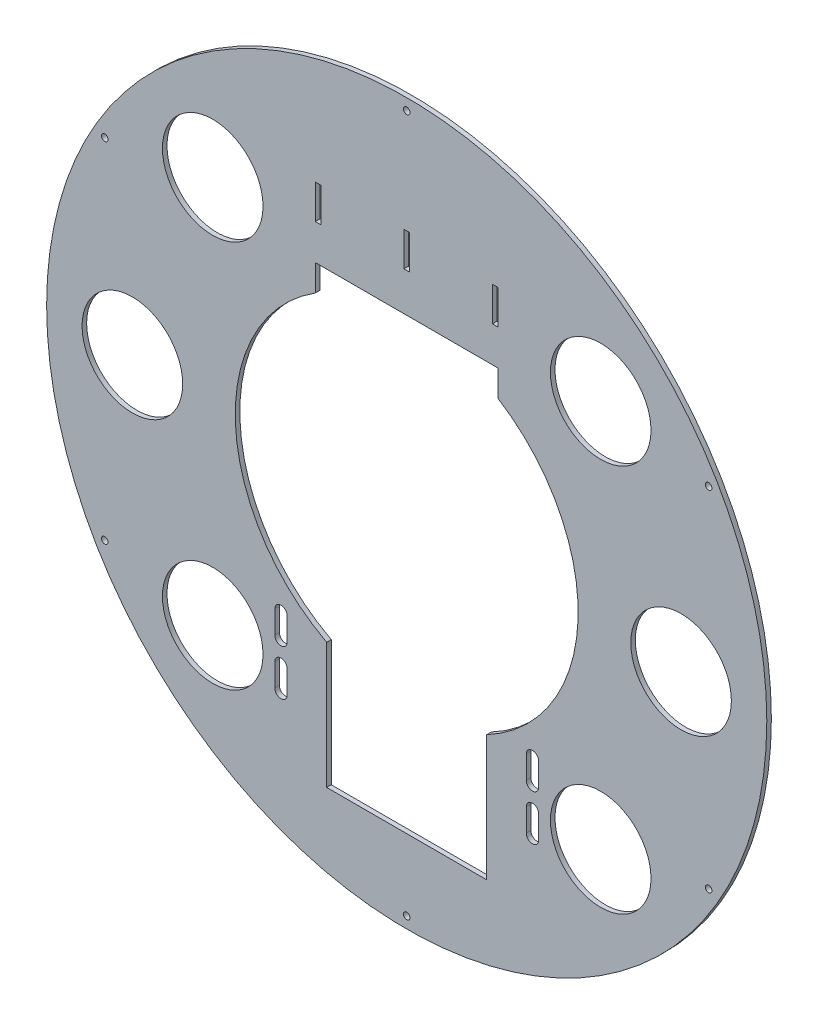
SolidWorks part; units mm, degrees
ref_plane "Front Plane" through (0, 0, 0) normal (0, 0, 1) x (1, 0, 0)
ref_plane "Top Plane" through (0, 0, 0) normal (0, 1, 0) x (1, 0, 0)
ref_plane "Right Plane" through (0, 0, 0) normal (1, 0, 0) x (0, 0, -1)
sketch "Sketch1" plane through (0, 0, 0) normal (0, 0, 1) x (-1, 0, 0)
  arc A4 (0, -200.025) -> (0, 200.025) centre (0, 0) ccw
  arc A5 (0, 200.025) -> (0, -200.025) centre (0, 0) ccw
  arc A16 (167.6449, 98.6533) -> (167.8101, 95.0217) centre (167.7275, 96.8375) ccw
  arc A17 (167.8101, 95.0217) -> (167.6449, 98.6533) centre (167.7275, 96.8375) ccw
  arc A18 (-1.6138, 194.5114) -> (1.6138, 192.8386) centre (0, 193.675) ccw
  arc A19 (1.6138, 192.8386) -> (-1.6138, 194.5114) centre (0, 193.675) ccw
  arc A20 (-169.2587, 95.8581) -> (-166.1962, 97.8169) centre (-167.7275, 96.8375) ccw
  arc A21 (-166.1962, 97.8169) -> (-169.2587, 95.8581) centre (-167.7275, 96.8375) ccw
  arc A22 (-167.6449, -98.6533) -> (-167.8101, -95.0217) centre (-167.7275, -96.8375) ccw
  arc A23 (-167.8101, -95.0217) -> (-167.6449, -98.6533) centre (-167.7275, -96.8375) ccw
  arc A24 (1.6138, -194.5114) -> (-1.6138, -192.8386) centre (0, -193.675) ccw
  arc A25 (-1.6138, -192.8386) -> (1.6138, -194.5114) centre (0, -193.675) ccw
  arc A26 (169.2587, -95.8581) -> (166.1962, -97.8169) centre (167.7275, -96.8375) ccw
  arc A27 (166.1962, -97.8169) -> (169.2587, -95.8581) centre (167.7275, -96.8375) ccw
  point P0 (0, 193.675)
sketch "Sketch2" plane through (0, 0, 0) normal (0, 0, 1) x (1, 0, 0)
  line L0 (-69.85, -82.55) -> (-69.85, -95.25) construction
  line L1 (-44.45, -84.2423) -> (44.45, -84.2423)
  line L2 (-44.45, -84.2423) -> (-44.45, -154.0923)
  line L3 (-44.45, -154.0923) -> (44.45, -154.0923)
  line L4 (44.45, -84.2423) -> (44.45, -154.0923)
  line L5 (-66.421, -82.55) -> (-66.421, -95.25)
  line L6 (-73.279, -82.55) -> (-73.279, -95.25)
  line L7 (69.85, -82.55) -> (69.85, -95.25) construction
  line L8 (73.279, -82.55) -> (73.279, -95.25)
  line L9 (66.421, -82.55) -> (66.421, -95.25)
  line L10 (-69.85, -107.95) -> (-69.85, -120.65) construction
  line L11 (-66.421, -107.95) -> (-66.421, -120.65)
  line L12 (-73.279, -107.95) -> (-73.279, -120.65)
  line L13 (69.85, -107.95) -> (69.85, -120.65) construction
  line L14 (73.279, -107.95) -> (73.279, -120.65)
  line L15 (66.421, -107.95) -> (66.421, -120.65)
  line L16 (-76.9302, -101.6) -> (80.7091, -101.6) construction
  line L18 (-50.8, 95.25) -> (50.8, 95.25)
  line L19 (-50.8, 95.25) -> (-50.8, 80.5725)
  line L20 (-50.8, 80.5725) -> (50.8, 80.5725)
  line L21 (50.8, 95.25) -> (50.8, 80.5725)
  circle A0 centre (0, 0) radius 95.25
  arc A1 (-66.421, -82.55) -> (-73.279, -82.55) centre (-69.85, -82.55) ccw
  arc A2 (1.6138, -194.5114) -> (-1.6138, -192.8386) centre (0, -193.675) ccw
  arc A3 (-1.6138, -192.8386) -> (1.6138, -194.5114) centre (0, -193.675) ccw
  arc A4 (1.6138, -194.5114) -> (-1.6138, -192.8386) centre (0, -193.675) ccw
  arc A5 (-1.6138, -192.8386) -> (1.6138, -194.5114) centre (0, -193.675) ccw
  arc A6 (-167.6449, -98.6533) -> (-167.8101, -95.0217) centre (-167.7275, -96.8375) ccw
  arc A7 (-167.8101, -95.0217) -> (-167.6449, -98.6533) centre (-167.7275, -96.8375) ccw
  arc A8 (-167.6449, -98.6533) -> (-167.8101, -95.0217) centre (-167.7275, -96.8375) ccw
  arc A9 (-167.8101, -95.0217) -> (-167.6449, -98.6533) centre (-167.7275, -96.8375) ccw
  arc A10 (0, 200.025) -> (0, -200.025) centre (0, 0) ccw
  arc A11 (0, -200.025) -> (0, 200.025) centre (0, 0) ccw
  arc A12 (0, 200.025) -> (0, -200.025) centre (0, 0) ccw
  arc A13 (0, -200.025) -> (0, 200.025) centre (0, 0) ccw
  arc A14 (167.6449, 98.6533) -> (167.8101, 95.0217) centre (167.7275, 96.8375) ccw
  arc A15 (167.8101, 95.0217) -> (167.6449, 98.6533) centre (167.7275, 96.8375) ccw
  arc A16 (167.6449, 98.6533) -> (167.8101, 95.0217) centre (167.7275, 96.8375) ccw
  arc A17 (167.8101, 95.0217) -> (167.6449, 98.6533) centre (167.7275, 96.8375) ccw
  arc A18 (169.2587, -95.8581) -> (166.1962, -97.8169) centre (167.7275, -96.8375) ccw
  arc A19 (166.1962, -97.8169) -> (169.2587, -95.8581) centre (167.7275, -96.8375) ccw
  arc A20 (169.2587, -95.8581) -> (166.1962, -97.8169) centre (167.7275, -96.8375) ccw
  arc A21 (166.1962, -97.8169) -> (169.2587, -95.8581) centre (167.7275, -96.8375) ccw
  arc A22 (-169.2587, 95.8581) -> (-166.1962, 97.8169) centre (-167.7275, 96.8375) ccw
  arc A23 (-166.1962, 97.8169) -> (-169.2587, 95.8581) centre (-167.7275, 96.8375) ccw
  arc A24 (-169.2587, 95.8581) -> (-166.1962, 97.8169) centre (-167.7275, 96.8375) ccw
  arc A25 (-166.1962, 97.8169) -> (-169.2587, 95.8581) centre (-167.7275, 96.8375) ccw
  arc A26 (-1.6138, 194.5114) -> (1.6138, 192.8386) centre (0, 193.675) ccw
  arc A27 (1.6138, 192.8386) -> (-1.6138, 194.5114) centre (0, 193.675) ccw
  arc A28 (-1.6138, 194.5114) -> (1.6138, 192.8386) centre (0, 193.675) ccw
  arc A29 (1.6138, 192.8386) -> (-1.6138, 194.5114) centre (0, 193.675) ccw
  arc A30 (-73.279, -95.25) -> (-66.421, -95.25) centre (-69.85, -95.25) ccw
  arc A31 (73.279, -82.55) -> (66.421, -82.55) centre (69.85, -82.55) ccw
  arc A32 (66.421, -95.25) -> (73.279, -95.25) centre (69.85, -95.25) ccw
  arc A33 (-66.421, -107.95) -> (-73.279, -107.95) centre (-69.85, -107.95) ccw
  arc A34 (-73.279, -120.65) -> (-66.421, -120.65) centre (-69.85, -120.65) ccw
  arc A35 (73.279, -107.95) -> (66.421, -107.95) centre (69.85, -107.95) ccw
  arc A36 (66.421, -120.65) -> (73.279, -120.65) centre (69.85, -120.65) ccw
  point P33 (-69.85, -88.9)
  point P34 (0, -84.2423)
  point P43 (69.85, -88.9)
  point P48 (-69.85, -114.3)
  point P55 (69.85, -114.3)
  point P68 (0, 0)
  point P69 (0, 0)
  dimension "D8" = 88.9
  dimension "D10" = 190.5
  dimension "D9" = 69.85
  dimension "D11" = 6.858
  dimension "D12" = 6.858
  dimension "D13" = 139.7
  dimension "D14" = 69.85
  dimension "D15" = 12.7
  dimension "D16" = 6.858
  dimension "D17" = 6.858
  dimension "D18" = 25.4
  dimension "D19" = 12.7
  dimension "D20" = 101.6
  dimension "D21" = 101.6
  dimension "D1" = 0
  dimension "D2" = 0
  dimension "D3" = 0
  dimension "D4" = 0
  dimension "D5" = 0
  dimension "D6" = 0
  dimension "D7" = 0
extrude "Boss-Extrude1" add sketch "Sketch2" along normal blind 2.54 contours A12 A13 A29 A28 A25 A24 A21 A20 A17 A16 A0 L4 L3 L2 A5 A4 A9 A8
sketch "Sketch5" plane through (0, 0, 0) normal (0, 0, -1) x (-1, 0, 0)
  line L8 (-50.8, -114.9516) -> (-50.8, -134.0016)
  line L9 (-50.8, -134.0016) -> (-47.625, -134.0016)
  line L10 (-47.625, -134.0016) -> (-47.625, -114.9516)
  line L11 (-47.625, -114.9516) -> (-50.8, -114.9516)
  line L12 (47.625, -114.9516) -> (47.625, -134.0016)
  line L13 (47.625, -134.0016) -> (50.8, -134.0016)
  line L14 (50.8, -134.0016) -> (50.8, -114.9516)
  line L15 (50.8, -114.9516) -> (47.625, -114.9516)
  line L16 (-371.3275, 0) -> (-517.8618, 0)
  line L17 (50.8, 114.9516) -> (47.625, 114.9516)
  line L18 (50.8, 134.0016) -> (50.8, 114.9516)
  line L19 (47.625, 134.0016) -> (50.8, 134.0016)
  line L20 (47.625, 114.9516) -> (47.625, 134.0016)
  line L21 (-47.625, 114.9516) -> (-50.8, 114.9516)
  line L22 (-47.625, 134.0016) -> (-47.625, 114.9516)
  line L23 (-50.8, 134.0016) -> (-47.625, 134.0016)
  line L24 (-50.8, 114.9516) -> (-50.8, 134.0016)
  line L25 (1.5875, 116.8399) -> (-1.5875, 116.8399)
  line L26 (1.5875, 135.8899) -> (1.5875, 116.8399)
  line L27 (-1.5875, 135.8899) -> (1.5875, 135.8899)
  line L28 (-1.5875, 116.8399) -> (-1.5875, 135.8899)
  circle A1 centre (0, 0) radius 200.025
  point P11 (-49.2125, -114.9516)
  point P22 (0, 0)
  point P28 (0, 0)
  point P29 (0, 116.8399)
  dimension "D1" = 95.25
  dimension "D2" = 3.175
  dimension "D3" = 3.175
  dimension "D4" = 19.05
  dimension "D5" = 19.05
  dimension "D6" = 47.625
  dimension "D7" = 114.9516
  dimension "D8" = 19.05
  dimension "D9" = 3.175
extrude "Cut-Extrude1" cut sketch "Sketch5" against normal blind 3.175 contours L20 L17 L18 L19 | L28 L25 L26 L27 | L24 L21 L22 L23
sketch "Sketch6" plane through (0, 0, 0) normal (0, 0, -1) x (-1, 0, 0)
  circle A0 centre (-152.4, 0) radius 27.9381
  circle A1 centre (-107.7631, 107.7631) radius 27.9381
  circle A3 centre (107.7631, 107.7631) radius 27.9381
  circle A4 centre (152.4, 0) radius 27.9381
  circle A5 centre (107.7631, -107.7631) radius 27.9381
  circle A7 centre (-107.7631, -107.7631) radius 27.9381
  circle A8 centre (0, 152.4) radius 27.9381 [skipped]
  circle A9 centre (0, -152.4) radius 27.9381 [skipped]
  point P20 (0, 0)
  dimension "D1" = 152.4
  dimension "D2" = 8
extrude "Cut-Extrude2" cut sketch "Sketch6" against normal blind 3.175
